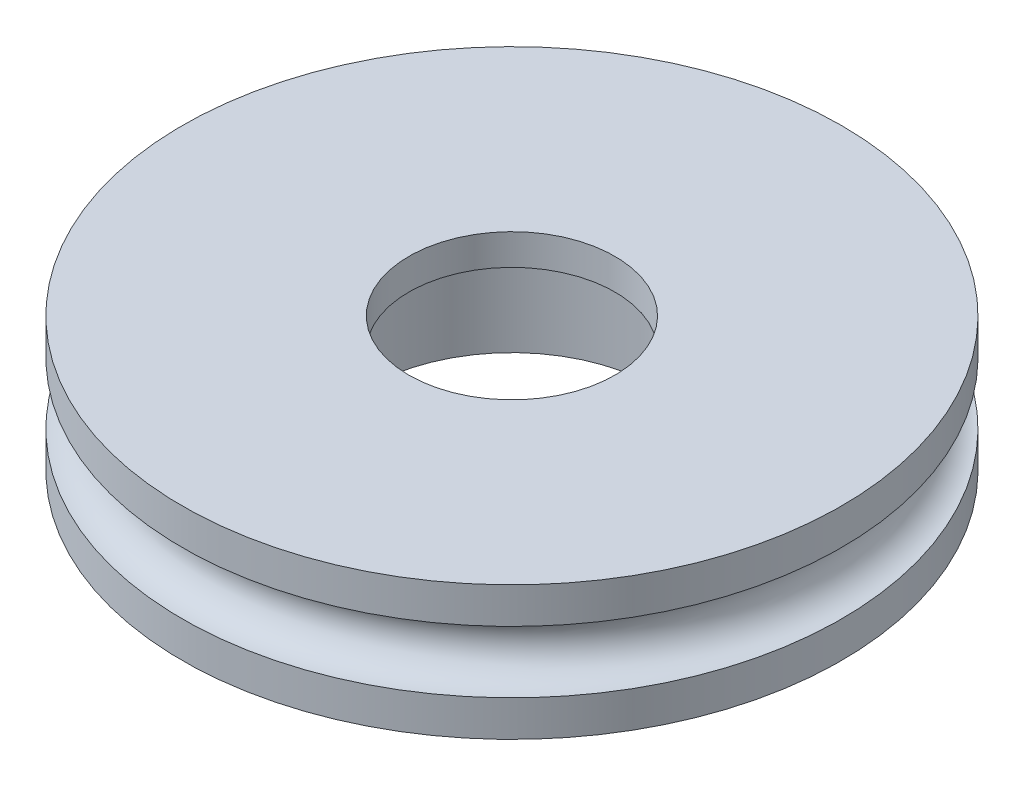
SolidWorks part; units mm, degrees
ref_plane "Front Plane" through (0, 0, 0) normal (0, 0, 1) x (1, 0, 0)
ref_plane "Top Plane" through (0, 0, 0) normal (0, 1, 0) x (1, 0, 0)
ref_plane "Right Plane" through (0, 0, 0) normal (1, 0, 0) x (0, 0, -1)
sketch "Sketch1" plane through (0, 0, 0) normal (0, 1, 0) x (1, 0, 0)
  circle A2 centre (0, 0) radius 3.5
  circle A3 centre (0, 0) radius 8
  dimension "D1" = 7
  dimension "D2" = 16
extrude "Boss-Extrude1" add sketch "Sketch1" along normal mid plane 3.25
sketch "Sketch2" plane through (0, 0, 0) normal (1, 0, 0) x (0, 0, -1)
  line L0 (-8, -1.625) -> (-8, -0.75) construction
  line L1 (-8, 1.625) -> (-8, -1.625) construction
  line L2 (-8, 1.625) -> (-8, 0.75) construction
  line L3 (-8, 0.75) -> (-8, -0.75)
  line L4 (-8, -1.625) -> (8, -1.625) construction
  arc A0 (-8, 0.75) -> (-8, -0.75) centre (-8, 0) cw
  dimension "D1" = 1.5
  dimension "D2" = 0.75
  dimension "D3" = 0.875
revolve "Cut-Revolve1" cut sketch "Sketch2" angle 360 about axis through (0, 1.625, 0) along (0, -1, 0)
sketch "Sketch3" plane through (0, 1.625, 0) normal (0, 1, 0) x (1, 0, 0)
  circle A0 centre (0, 0) radius 3.5
  circle A1 centre (0, 0) radius 2.5
  dimension "D1" = 5
  dimension "D2" = 7
extrude "Boss-Extrude2" add sketch "Sketch3" against normal blind 0.75
